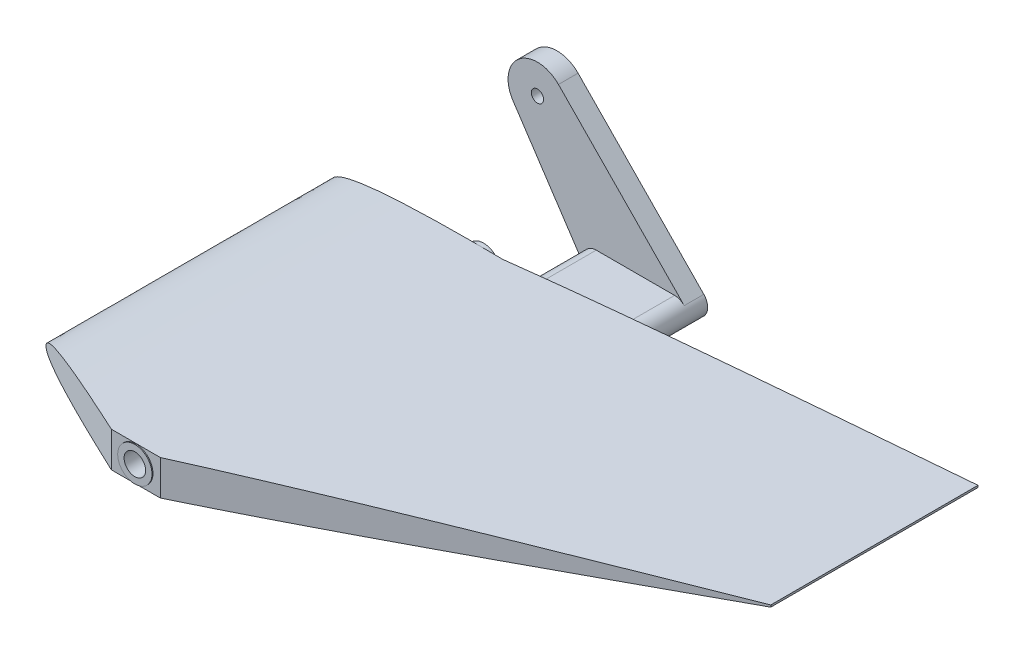
SolidWorks part; units mm, degrees
ref_plane "Front Plane" through (0, 0, 0) normal (0, 0, 1) x (1, 0, 0)
ref_plane "Top Plane" through (0, 0, 0) normal (0, 1, 0) x (1, 0, 0)
ref_plane "Right Plane" through (0, 0, 0) normal (1, 0, 0) x (0, 0, -1)
sketch "Sketch1" plane through (0, 0, 0) normal (0, 0, 1) x (1, 0, 0)
  line L0 (-15, 0) -> (-15, -2.6956) construction
  line L1 (0, 0) -> (-24865.1116, 0) construction
  line L2 (-19.5151, 1.8079) -> (14.7756, 1.8079) construction
  line L3 (-15, 0) -> (44.9999, 0)
  line L4 (44.9999, 0) -> (44.9999, 0.1)
  spline S0 degree 3 poles (-15, 0) (-15, 3.231) (19.0771, 1.4031) (44.9999, 0.1) knots 0 0 0 0 1 1 1 1
  dimension "D1" = 1.8079
  dimension "D2" = 60
  dimension "D3" = 0.1
  dimension "D4" = 15
extrude "Boss-Extrude1" add sketch "Sketch1" along normal blind 50 contours S0 L4 L3
mirror "Mirror1" about plane through (-15, 0, 50) normal (0, 1, 0) of "Boss-Extrude1"
sketch "Sketch2" plane through (0, 0, 0) normal (0, 1, 0) x (1, 0, 0)
  line L0 (-27.642, -50) -> (50.6593, -50) construction
  line L1 (-15, -50) -> (44.9999, -50) construction
  line L2 (-26.5228, -38.798) -> (-2.5, -50)
  line L3 (-2.5, -50) -> (2.5, -50)
  line L4 (2.5, -50) -> (51.7922, -27.0147)
  line L5 (51.7922, -27.0147) -> (51.7922, -55.1159)
  line L6 (51.7922, -55.1159) -> (-26.5228, -55.1159)
  line L7 (-26.5228, -55.1159) -> (-26.5228, -38.798)
  line L8 (-15, -62.14) -> (-15, 22.2853) construction
  line L9 (-15, -50) -> (-15, 0) construction
  line L10 (-24.9323, -15) -> (52.3257, -15) construction
  line L11 (0, -50) -> (0, 20) construction
  line L12 (-2.5, -15) -> (2.5, -15)
  line L13 (-2.5, -15) -> (-22.8232, -15)
  line L14 (-22.8232, -15) -> (-22.8232, 7.1094)
  line L15 (-22.8232, 7.1094) -> (50.3549, 7.1094)
  line L16 (50.3549, 7.1094) -> (50.3549, -8.2744)
  line L17 (50.3549, -8.2744) -> (2.5, -15)
  point P14 (0, -50)
  point P23 (0, -15)
  dimension "D1" = 15
  dimension "D2" = 5
  dimension "D3" = 25
  dimension "D4" = 25
  dimension "D5" = 35
  dimension "D6" = 8
  dimension "D7" = 0
extrude "Cut-Extrude1" cut sketch "Sketch2" against normal through all both and the other way through all
sketch "Sketch3" plane through (0, 0, 50) normal (0, 0, 1) x (1, 0, 0)
  line L0 (0, -4.0569) -> (0, 6.5289) construction
  line L1 (-3.4021, 0) -> (0.829, 0) construction
  line L2 (-2.5, -1.7987) -> (-2.5, 1.7987) construction
  line L3 (2.5, -1.7911) -> (2.5, 1.7911) construction
  line L4 (-9.2245, -1.8079) -> (7.7387, -1.8079) construction
  line L5 (-11.2019, 1.8079) -> (8.6925, 1.8079) construction
  circle A0 centre (0, 0) radius 1.75
  spline S6 degree 3 poles (-2.5, 1.7987) (-0.938, 1.8135) (0.7355, 1.81) (2.5, 1.7911) knots 0.380927 0.380927 0.380927 0.380927 0.45968 0.45968 0.45968 0.45968 construction
  spline S7 degree 3 poles (-2.5, -1.7987) (-0.938, -1.8135) (0.7355, -1.81) (2.5, -1.7911) knots 0.380927 0.380927 0.380927 0.380927 0.45968 0.45968 0.45968 0.45968 construction
  dimension "D1" = 3.5
extrude "Boss-Extrude2" add sketch "Sketch3" along normal blind 0.1
sketch "Sketch5" plane through (0, 0, 15) normal (0, 0, -1) x (-1, 0, 0)
  circle A0 centre (0, 0) radius 1.75 construction
  circle A1 centre (0, 0) radius 1.75
extrude "Boss-Extrude3" add sketch "Sketch5" along normal blind 0.5
sketch "Sketch4" plane through (0, 0, 50.1) normal (0, 0, 1) x (1, 0, 0)
  circle A0 centre (0, 0) radius 1.1
  dimension "D1" = 2.2
extrude "Cut-Extrude2" cut sketch "Sketch4" against normal through all
ref_plane "Plane1" through (0, 0, 9) normal (0, 0, -1) x (-1, 0, 0)
sketch "Sketch6" plane through (0, 0, 9) normal (0, 0, -1) x (-1, 0, 0)
  line L0 (-6, 0) -> (-14, 0) construction
  line L1 (-6, -1.375) -> (-14, -1.375)
  line L2 (-6, 1.375) -> (-14, 1.375)
  arc A0 (-6, -1.375) -> (-6, 1.375) centre (-6, 0) ccw
  arc A1 (-14, 1.375) -> (-14, -1.375) centre (-14, 0) ccw
  point P0 (-9.2742, 0)
  point P4 (-10, 0)
  dimension "D1" = 2.75
  dimension "D2" = 8
  dimension "D3" = 6
extrude "Boss-Extrude4" add sketch "Sketch6" against normal up to next
sketch "Sketch7" plane through (0, 0, 9) normal (0, 0, -1) x (-1, 0, 0)
  line L0 (-4.8537, -0.7593) -> (2.501, 10.3432)
  line L1 (-2.1455, 14.0968) -> (-14.9834, 0.9611)
  line L2 (-14, -1.375) -> (-6, -1.375) construction
  line L3 (-14, -1.375) -> (-6, -1.375) construction
  line L4 (-6, -1.375) -> (-14, -1.375)
  arc A0 (2.501, 10.3432) -> (-2.1455, 14.0968) centre (0, 12) ccw
  arc A1 (-6, -1.375) -> (-6, 1.375) centre (-6, 0) ccw construction
  arc A2 (-14, 1.375) -> (-14, -1.375) centre (-14, 0) ccw construction
  arc A3 (-6, -1.375) -> (-6, 1.375) centre (-6, 0) ccw construction
  arc A4 (-14, 1.375) -> (-14, -1.375) centre (-14, 0) ccw construction
  arc A5 (-4.8537, -0.7593) -> (-6, -1.375) centre (-6, 0) cw
  arc A6 (-14.9834, 0.9611) -> (-14, -1.375) centre (-14, 0) ccw
  dimension "D1" = 3
  dimension "D2" = 12
extrude "Boss-Extrude5" add sketch "Sketch7" along normal blind 2
sketch "Sketch8" plane through (0, 0, 7) normal (0, 0, -1) x (-1, 0, 0)
  circle A0 centre (0, 12) radius 0.625
  arc A1 (2.501, 10.3432) -> (-2.1455, 14.0968) centre (0, 12) ccw construction
  dimension "D1" = 1.25
extrude "Cut-Extrude3" cut sketch "Sketch8" against normal through all
